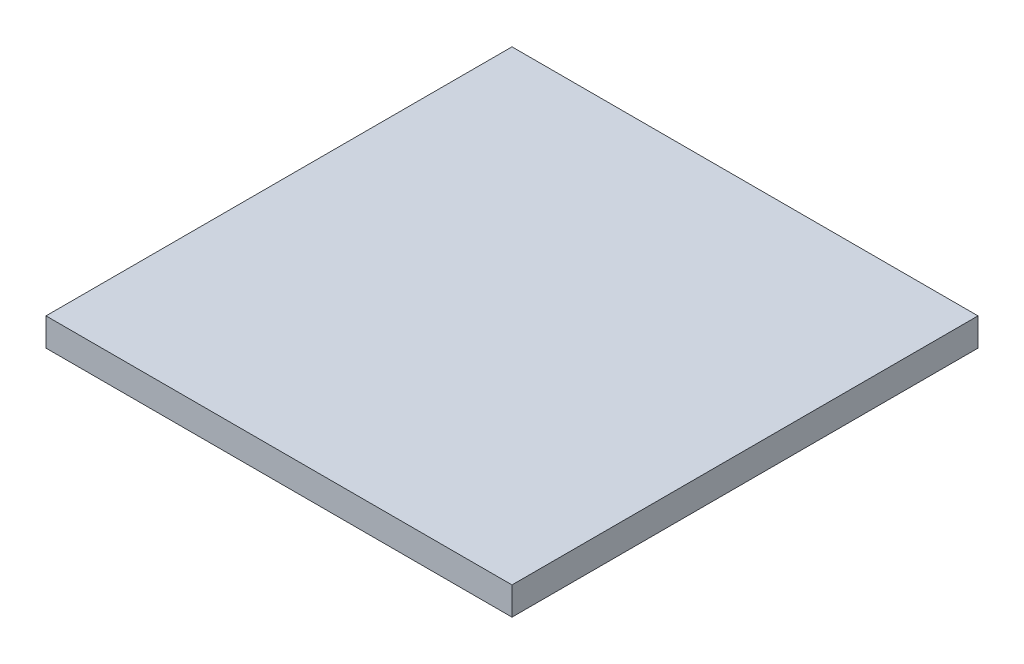
SolidWorks part; units mm, degrees
material "PE High Density"
ref_plane "Front Plane" through (0, 0, 0) normal (0, 0, 1) x (1, 0, 0)
ref_plane "Top Plane" through (0, 0, 0) normal (0, 1, 0) x (1, 0, 0)
ref_plane "Right Plane" through (0, 0, 0) normal (1, 0, 0) x (0, 0, -1)
sketch "Sketch1" plane through (0, 0, 0) normal (0, 1, 0) x (1, 0, 0)
  line L0 (-250, 250) -> (250, 250)
  line L1 (-250, 250) -> (-250, -250)
  line L2 (250, 250) -> (250, -250)
  line L3 (-250, -250) -> (250, -250)
  line L4 (-250, 250) -> (250, -250) construction
  line L5 (250, 250) -> (-250, -250) construction
  point P1 (0, 0)
  dimension "D1" = 500
  dimension "D2" = 500
extrude "Boss-Extrude1" add sketch "Sketch1" along normal blind 30
